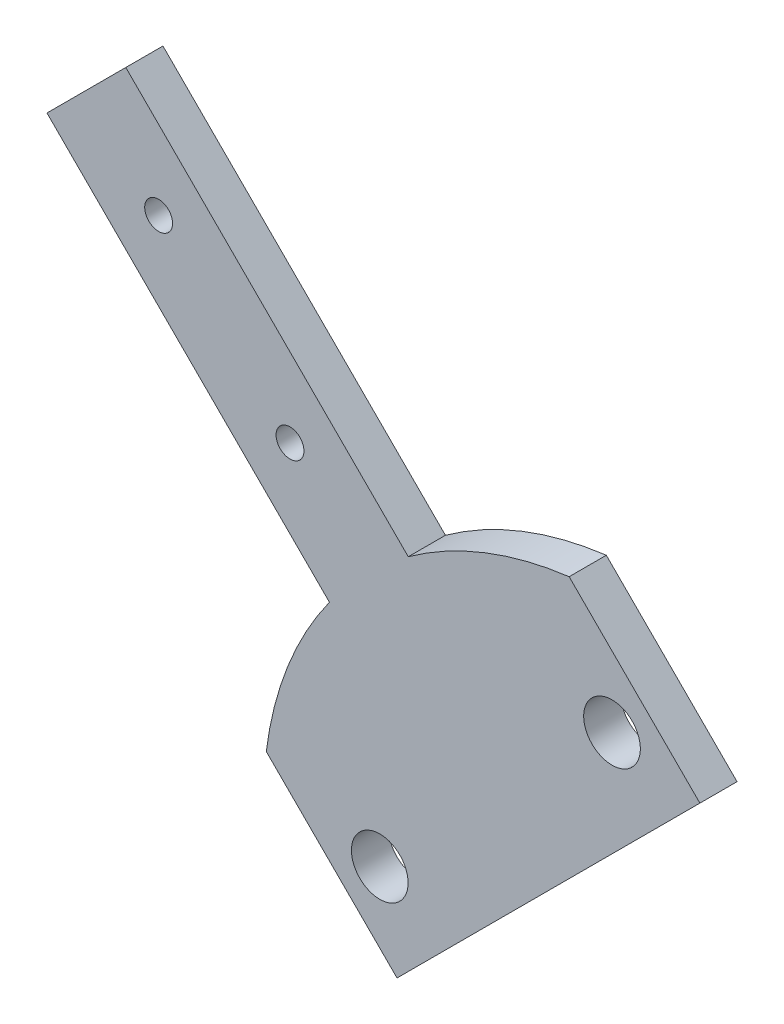
SolidWorks part; units mm, degrees
ref_plane "Front Plane" through (0, 0, 0) normal (0, 0, 1) x (1, 0, 0)
ref_plane "Top Plane" through (0, 0, 0) normal (0, 1, 0) x (1, 0, 0)
ref_plane "Right Plane" through (0, 0, 0) normal (1, 0, 0) x (0, 0, -1)
sketch "Sketch2" plane through (0, 0, 0) normal (0, 0, 1) x (1, 0, 0)
  line L0 (-25, 0) -> (0, 25) construction
  line L1 (-23.1426, -9.4563) -> (9.4563, 23.1426)
  line L5 (-56.5805, 56.5805) -> (-26.1749, 26.1749) construction
  line L6 (-23.1426, -9.4563) -> (-37.2148, 4.616)
  line L7 (9.4563, 23.1426) -> (-4.616, 37.2148)
  line L10 (-30.4175, 21.9323) -> (-60.8231, 52.3378)
  line L11 (-21.9323, 30.4175) -> (-52.3378, 60.8231)
  line L12 (-60.8231, 52.3378) -> (-52.3378, 60.8231)
  circle A0 centre (0, 0) radius 25 construction
  circle A1 centre (0, 25) radius 3.05
  circle A3 centre (-25, 0) radius 3.05
  circle A4 centre (0, 0) radius 25 construction
  circle A5 centre (0, 0) radius 37.5 construction
  arc A6 (-37.2148, 4.616) -> (-30.4175, 21.9323) centre (0, 0) cw
  arc A7 (-4.616, 37.2148) -> (-21.9323, 30.4175) centre (0, 0) ccw
  circle A8 centre (-48.8023, 48.8023) radius 1.5
  circle A9 centre (-34.6602, 34.6602) radius 1.5
  point P9 (0, 0)
  point P12 (0, 0)
  point P15 (-26.5165, 26.5165)
  dimension "D1" = 50
  dimension "D2" = 6.1
  dimension "D3" = 2
  dimension "D4" = 75
  dimension "D9" = 3
  dimension "D10" = 3
  dimension "D5" = 8
  dimension "D6" = 11
  dimension "D8" = 43
  dimension "D11" = 20
extrude "Boss-Extrude1" add sketch "Sketch2" along normal blind 4
